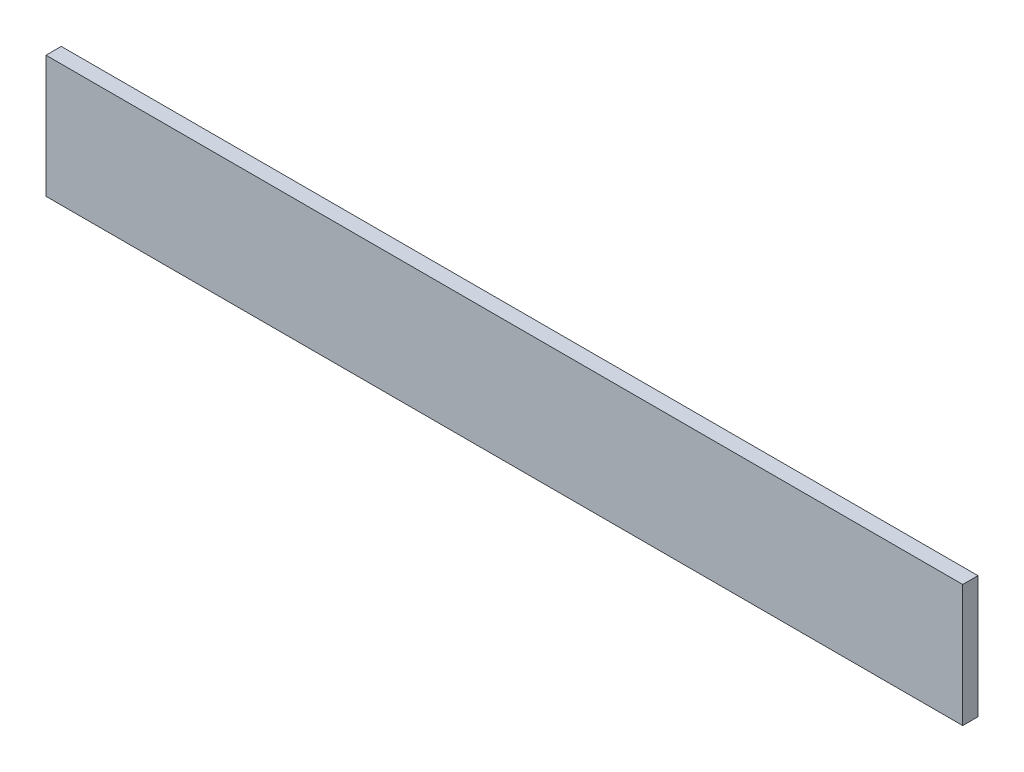
SolidWorks part; units mm, degrees
ref_plane "Plan de face" through (0, 0, 0) normal (0, 0, 1) x (1, 0, 0)
ref_plane "Plan de dessus" through (0, 0, 0) normal (0, 1, 0) x (1, 0, 0)
ref_plane "Plan de droite" through (0, 0, 0) normal (1, 0, 0) x (0, 0, -1)
sketch "Esquisse1" plane through (0, 0, 0) normal (0, 0, 1) x (1, 0, 0)
  line L1 (-60, 8) -> (60, 8)
  line L2 (-60, 8) -> (-60, -8)
  line L3 (-60, -8) -> (60, -8)
  line L4 (60, 8) -> (60, -8)
  line L5 (-60, 8) -> (60, -8) construction
  line L6 (-60, -8) -> (60, 8) construction
  point P0 (0, 0)
  dimension "D1" = 16
  dimension "D2" = 120
extrude "Boss.-Extru.1" add sketch "Esquisse1" along normal blind 2
